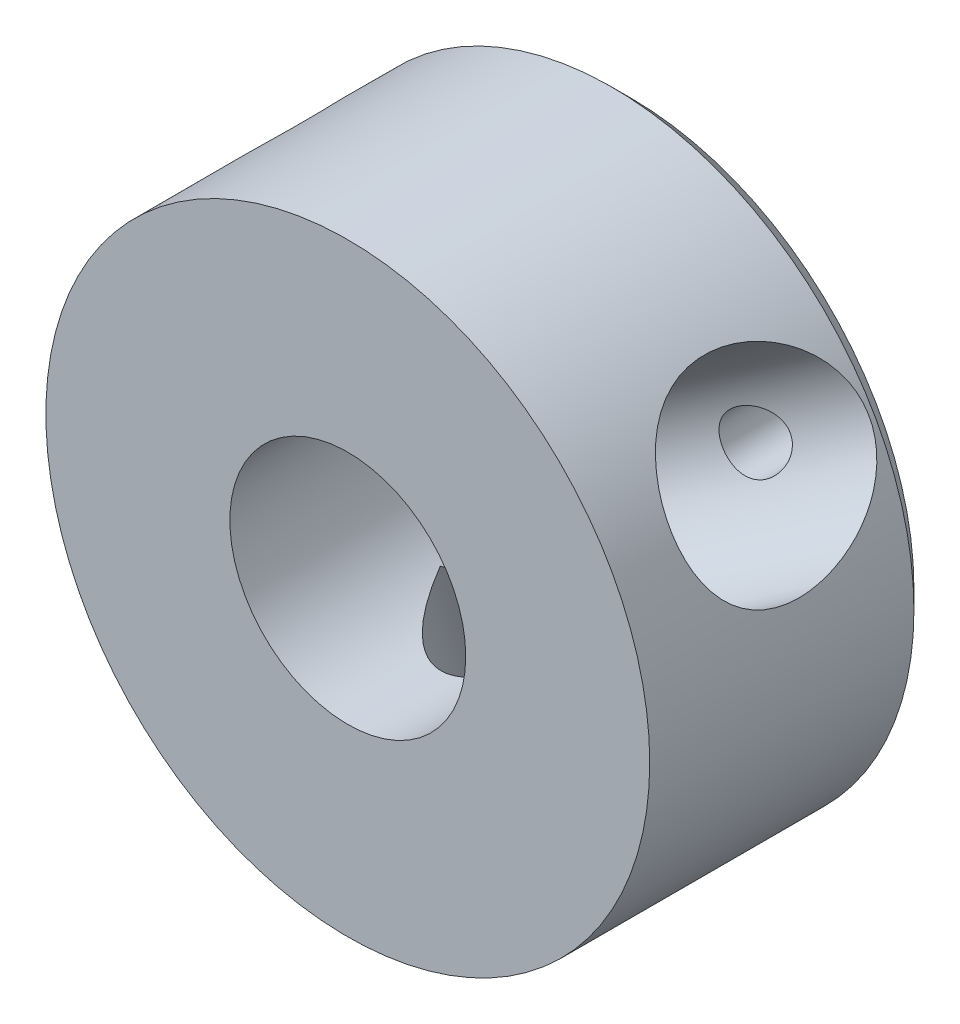
SolidWorks part; units mm, degrees
material "Plain Carbon Steel"
ref_plane "Front Plane" through (0, 0, 0) normal (0, 0, 1) x (1, 0, 0)
ref_plane "Top Plane" through (0, 0, 0) normal (0, 1, 0) x (1, 0, 0)
ref_plane "Right Plane" through (0, 0, 0) normal (1, 0, 0) x (0, 0, -1)
sketch "Sketch1" plane through (0, 0, 0) normal (0, 0, 1) x (1, 0, 0)
  circle A0 centre (0, 0) radius 32
  circle A1 centre (0, 0) radius 12.5
  dimension "D1" = 64
  dimension "D2" = 25
extrude "Boss-Extrude1" add sketch "Sketch1" along normal mid plane 30
sketch "Sketch5" plane through (0, 0, 0) normal (1, 0, 0) x (0, 0, -1)
  line L0 (-16.5772, 0) -> (33.3445, 0) construction
  line L1 (28.7595, 0) -> (-28.7595, 0) construction
  line L3 (33.3445, 0) -> (12.5012, 0) construction
  line L4 (33.3445, 0) -> (-17.1534, -16.4078) construction
  point P5 (-17.1534, -16.4078)
  dimension "D1" = 18
ref_plane "Plane3" through (0, -9.7997, -3.1841) normal (0, 0.9511, 0.309) x (0, -0.309, 0.9511)
sketch "Sketch2" plane through (0, -9.8195, -3.1231) normal (0, 0.9511, 0.309) x (1, 0, 0)
  line L0 (0, -28.6953) -> (0, 28.8237) construction
  circle A0 centre (0, -7.9358) radius 10
  dimension "D1" = 20
  dimension "D2" = 20
  dimension "D3" = 8
extrude "Cut-Extrude1" cut sketch "Sketch2" against normal through all
pattern_circular "CirPattern1" count 3 over 360 about axis through (0, 0, 0) along (0, 0, 1) of "Cut-Extrude1"
sketch "Sketch4" plane through (0, 0, -15) normal (0, 0, 1) x (1, 0, 0)
  line L0 (0, 0) -> (0, -32) construction
  line L2 (0, 0) -> (-35.061, 0) construction
  line L3 (0, -32) -> (0, -22)
  circle A0 centre (0, 0) radius 32 construction
  circle A1 centre (0, -22) radius 3
  dimension "D1" = 270
extrude "Cut-Extrude3" cut sketch "Sketch4" along normal blind 11 contours A1
pattern_circular "CirPattern2" count 3 over 360 about axis through (0, 0, 0) along (0, 0, 1) of "Cut-Extrude3"
chamfer "Chamfer2" distance 2 angle 45 1 edges at (32, 0, -15)
